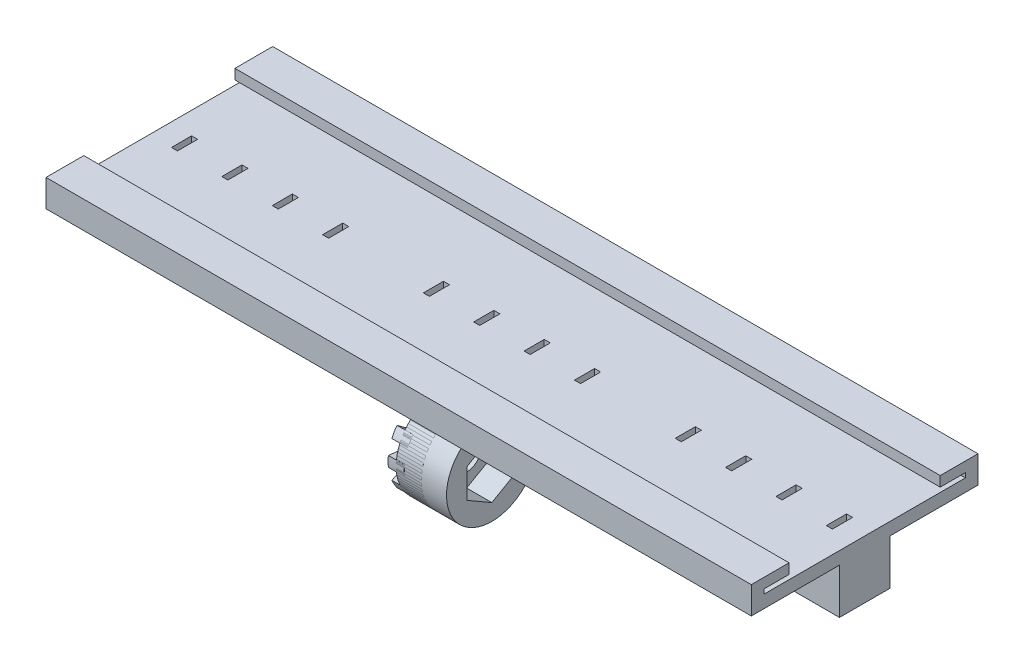
SolidWorks part; units mm, degrees
ref_plane "Alzado" through (0, 0, 0) normal (0, 0, 1) x (1, 0, 0)
ref_plane "Planta" through (0, 0, 0) normal (0, 1, 0) x (1, 0, 0)
ref_plane "Vista lateral" through (0, 0, 0) normal (1, 0, 0) x (0, 0, -1)
sketch "Croquis1" plane through (0, 0, 0) normal (0, 1, 0) x (1, 0, 0)
  line L1 (0, 0) -> (140, 0)
  line L2 (0, 0) -> (0, 45)
  line L3 (0, 45) -> (140, 45)
  line L4 (140, 0) -> (140, 45)
  dimension "D1" = 140
  dimension "D2" = 45
extrude "Saliente-Extruir1" add sketch "Croquis1" along normal blind 2.5
sketch "Croquis2" plane through (0, 2.5, 0) normal (0, 1, 0) x (1, 0, 0)
  line L0 (0, 42.5) -> (140, 42.5)
  line L1 (0, 45) -> (0, 0) construction
  line L2 (140, 0) -> (140, 45) construction
  line L3 (0, 22.5) -> (140, 22.5) construction
  line L4 (0, 45) -> (140, 45)
  line L5 (140, 45) -> (140, 42.5)
  line L6 (0, 45) -> (0, 42.5)
  line L7 (0, 0) -> (140, 0)
  line L8 (140, 0) -> (140, 2.5)
  line L9 (0, 2.5) -> (140, 2.5)
  line L10 (0, 0) -> (0, 2.5)
  dimension "D1" = 2.5
extrude "Saliente-Extruir2" add sketch "Croquis2" along normal blind 0.9
sketch "Croquis3" plane through (0, 3.4, 0) normal (0, 1, 0) x (1, 0, 0)
  line L0 (0, 45) -> (140, 45)
  line L1 (140, 45) -> (140, 37.5)
  line L2 (140, 2.5) -> (140, 42.5) construction
  line L3 (140, 37.5) -> (0, 37.5)
  line L4 (0, 42.5) -> (0, 2.5) construction
  line L5 (0, 37.5) -> (0, 45)
  line L6 (0, 22.5) -> (140, 22.5) construction
  line L7 (140, 7.5) -> (0, 7.5)
  line L8 (140, 0) -> (140, 7.5)
  line L9 (0, 0) -> (140, 0)
  line L10 (0, 7.5) -> (0, 0)
  dimension "D1" = 7.5
extrude "Saliente-Extruir3" add sketch "Croquis3" along normal blind 2
sketch "Croquis4" plane through (0, 0, 0) normal (0, -1, 0) x (1, 0, 0)
  line L0 (0, -22.5) -> (140, -22.5) construction
  line L1 (0, -45) -> (0, 0) construction
  line L2 (140, 0) -> (140, -45) construction
  line L4 (0, -27.5) -> (140, -27.5)
  line L5 (0, -27.5) -> (0, -17.5)
  line L6 (0, -17.5) -> (140, -17.5)
  line L7 (140, -27.5) -> (140, -17.5)
  line L8 (1.5, -26) -> (138.5, -26)
  line L9 (1.5, -26) -> (1.5, -19)
  line L10 (1.5, -19) -> (138.5, -19)
  line L11 (138.5, -26) -> (138.5, -19)
  point P10 (140, -22.5)
  point P15 (138.5, -22.5)
  dimension "D1" = 10
  dimension "D2" = 137
  dimension "D3" = 7
  dimension "D4" = 1.5
extrude "Saliente-Extruir4" add sketch "Croquis4" along normal blind 9
ref_plane "Plano1" through (70, 0, 0) normal (1, 0, 0) x (0, 0, -1)
sketch "Croquis6" plane through (70, 0, 0) normal (1, 0, 0) x (0, 0, -1)
  line L0 (17.5, -9) -> (-0.5, -9) construction
  line L1 (17.5, -9) -> (18.5, -9)
  line L2 (27.5, -9) -> (17.5, -9) construction
  line L3 (18.5, -9) -> (18.5, 1)
  line L4 (18.5, 1) -> (8.5, 1)
  line L5 (8.5, 1) -> (8.5, 0)
  line L7 (8.5, -14.75) -> (13.4796, -11.875)
  line L8 (13.4796, -11.875) -> (13.4796, -6.125)
  line L9 (13.4796, -6.125) -> (8.5, -3.25)
  line L10 (8.5, -3.25) -> (3.5204, -6.125)
  line L11 (3.5204, -6.125) -> (3.5204, -11.875)
  line L12 (3.5204, -11.875) -> (8.5, -14.75)
  circle A0 centre (8.5, -9) radius 9 construction
  circle A1 centre (8.5, -9) radius 5.75 construction
  circle A2 centre (8.5, -9) radius 4.9796 construction
  arc A3 (8.5, 0) -> (17.5, -9) centre (8.5, -9) ccw
  dimension "D1" = 18
  dimension "D5" = 11.5
  dimension "D6" = 9.9593
  dimension "D2" = 18
  dimension "D3" = 10
  dimension "D4" = 10
extrude "Saliente-Extruir5" add sketch "Croquis6" along normal blind 10
sketch "Croquis7" plane through (70, 0, 0) normal (-1, 0, 0) x (0, 0, 1)
  line L0 (-8.5, -18) -> (-8.5, 0) construction
  line L1 (-8.5, -9) -> (-7.1125, 3.1779) construction
  line L2 (-8.5, -9) -> (-9.8875, 3.1779) construction
  line L3 (-9.1792, -3.0386) -> (-9.5188, -0.0579)
  line L4 (-7.8208, -3.0386) -> (-7.4812, -0.0579)
  line L5 (-4.9311, -4.1769) -> (-3.1466, -1.7653)
  line L6 (-6.1075, -3.4976) -> (-4.9113, -0.7465)
  line L7 (-2.9976, -6.6075) -> (-0.2465, -5.4113)
  line L8 (-3.6769, -5.4311) -> (-1.2653, -3.6466)
  line L9 (-2.5386, -9.6792) -> (0.4421, -10.0188)
  line L10 (-2.5386, -8.3208) -> (0.4421, -7.9812)
  line L11 (-3.6769, -12.5689) -> (-1.2653, -14.3534)
  line L12 (-2.9976, -11.3925) -> (-0.2465, -12.5887)
  line L13 (-6.1075, -14.5024) -> (-4.9113, -17.2535)
  line L14 (-4.9311, -13.8231) -> (-3.1466, -16.2347)
  line L15 (-9.1792, -14.9614) -> (-9.5188, -17.9421)
  line L16 (-7.8208, -14.9614) -> (-7.4812, -17.9421)
  line L17 (-12.0689, -13.8231) -> (-13.8534, -16.2347)
  line L18 (-10.8925, -14.5024) -> (-12.0887, -17.2535)
  line L19 (-14.0024, -11.3925) -> (-16.7535, -12.5887)
  line L20 (-13.3231, -12.5689) -> (-15.7347, -14.3534)
  line L21 (-14.4614, -8.3208) -> (-17.4421, -7.9812)
  line L22 (-14.4614, -9.6792) -> (-17.4421, -10.0188)
  line L23 (-13.3231, -5.4311) -> (-15.7347, -3.6466)
  line L24 (-14.0024, -6.6075) -> (-16.7535, -5.4113)
  line L25 (-10.8925, -3.4976) -> (-12.0887, -0.7465)
  line L26 (-12.0689, -4.1769) -> (-13.8534, -1.7653)
  arc A0 (-17.5, -9) -> (-8.5, 0) centre (-8.5, -9) ccw construction
  circle A1 centre (-8.5, -9) radius 9 construction
  circle A2 centre (-8.5, -9) radius 3 construction
  circle A3 centre (-8.5, -9) radius 6 construction
  arc A4 (-9.1792, -3.0386) -> (-7.8208, -3.0386) centre (-8.5, -9) cw
  arc A5 (-9.5188, -0.0579) -> (-7.4812, -0.0579) centre (-8.5, -9) cw
  arc A6 (-4.9113, -0.7465) -> (-3.1466, -1.7653) centre (-8.5, -9) cw
  arc A7 (-6.1075, -3.4976) -> (-4.9311, -4.1769) centre (-8.5, -9) cw
  arc A8 (-1.2653, -3.6466) -> (-0.2465, -5.4113) centre (-8.5, -9) cw
  arc A9 (-3.6769, -5.4311) -> (-2.9976, -6.6075) centre (-8.5, -9) cw
  arc A10 (0.4421, -7.9812) -> (0.4421, -10.0188) centre (-8.5, -9) cw
  arc A11 (-2.5386, -8.3208) -> (-2.5386, -9.6792) centre (-8.5, -9) cw
  arc A12 (-0.2465, -12.5887) -> (-1.2653, -14.3534) centre (-8.5, -9) cw
  arc A13 (-2.9976, -11.3925) -> (-3.6769, -12.5689) centre (-8.5, -9) cw
  arc A14 (-3.1466, -16.2347) -> (-4.9113, -17.2535) centre (-8.5, -9) cw
  arc A15 (-4.9311, -13.8231) -> (-6.1075, -14.5024) centre (-8.5, -9) cw
  arc A16 (-7.4812, -17.9421) -> (-9.5188, -17.9421) centre (-8.5, -9) cw
  arc A17 (-7.8208, -14.9614) -> (-9.1792, -14.9614) centre (-8.5, -9) cw
  arc A18 (-12.0887, -17.2535) -> (-13.8534, -16.2347) centre (-8.5, -9) cw
  arc A19 (-10.8925, -14.5024) -> (-12.0689, -13.8231) centre (-8.5, -9) cw
  arc A20 (-15.7347, -14.3534) -> (-16.7535, -12.5887) centre (-8.5, -9) cw
  arc A21 (-13.3231, -12.5689) -> (-14.0024, -11.3925) centre (-8.5, -9) cw
  arc A22 (-17.4421, -10.0188) -> (-17.4421, -7.9812) centre (-8.5, -9) cw
  arc A23 (-14.4614, -9.6792) -> (-14.4614, -8.3208) centre (-8.5, -9) cw
  arc A24 (-16.7535, -5.4113) -> (-15.7347, -3.6466) centre (-8.5, -9) cw
  arc A25 (-14.0024, -6.6075) -> (-13.3231, -5.4311) centre (-8.5, -9) cw
  arc A26 (-13.8534, -1.7653) -> (-12.0887, -0.7465) centre (-8.5, -9) cw
  arc A27 (-12.0689, -4.1769) -> (-10.8925, -3.4976) centre (-8.5, -9) cw
  point P19 (0, 0)
  point P64 (-8.5, -9)
  dimension "D1" = 18
  dimension "D2" = 6
  dimension "D4" = 12
  dimension "D5" = 12
  dimension "D3" = 6.5
extrude "Saliente-Extruir20" add sketch "Croquis7" along normal mid plane 3.2 separate body
ref_plane "Plano3" through (75, 0, 0) normal (1, 0, 0) x (0, 0, -1)
sketch "Croquis9" plane through (75, 0, 0) normal (1, 0, 0) x (0, 0, -1)
  line L0 (-0.5, -9) -> (17.5, -9) construction
  arc A0 (8.5, 0) -> (17.5, -9) centre (8.5, -9) ccw construction
  circle A1 centre (8.5, -9) radius 9
  circle A2 centre (8.5, -9) radius 3
  dimension "D1" = 6
extrude "Saliente-Extruir24" add sketch "Croquis9" against normal blind 5 separate body
sketch "Croquis10" plane through (0, 0, 0) normal (0, -1, 0) x (1, 0, 0)
  line L0 (0, -22.5) -> (140, -22.5) construction
  line L1 (0, -17.5) -> (0, -27.5) construction
  line L2 (140, -27.5) -> (140, -17.5) construction
  line L3 (0, -22.5) -> (70, -22.5) construction
  line L4 (25, -22.5) -> (25, -53.1388) construction
  line L5 (34.4, -20.5) -> (35.6, -20.5)
  line L6 (34.4, -20.5) -> (34.4, -24.5)
  line L7 (34.4, -24.5) -> (35.6, -24.5)
  line L8 (35.6, -20.5) -> (35.6, -24.5)
  line L9 (34.4, -20.5) -> (35.6, -24.5) construction
  line L10 (34.4, -24.5) -> (35.6, -20.5) construction
  line L12 (24.4, -20.5) -> (25.6, -20.5)
  line L13 (24.4, -20.5) -> (24.4, -24.5)
  line L14 (24.4, -24.5) -> (25.6, -24.5)
  line L15 (25.6, -20.5) -> (25.6, -24.5)
  line L16 (24.4, -20.5) -> (25.6, -24.5) construction
  line L17 (24.4, -24.5) -> (25.6, -20.5) construction
  line L18 (14.4, -20.5) -> (15.6, -20.5)
  line L19 (14.4, -20.5) -> (14.4, -24.5)
  line L20 (14.4, -24.5) -> (15.6, -24.5)
  line L21 (15.6, -20.5) -> (15.6, -24.5)
  line L22 (14.4, -20.5) -> (15.6, -24.5) construction
  line L23 (14.4, -24.5) -> (15.6, -20.5) construction
  line L24 (70, -22.5) -> (70, -65.2648) construction
  line L25 (4.4, -20.5) -> (5.6, -20.5)
  line L26 (4.4, -20.5) -> (4.4, -24.5)
  line L27 (4.4, -24.5) -> (5.6, -24.5)
  line L28 (5.6, -20.5) -> (5.6, -24.5)
  line L29 (4.4, -20.5) -> (5.6, -24.5) construction
  line L30 (4.4, -24.5) -> (5.6, -20.5) construction
  line L31 (70, -12.87) -> (70, 12.87) construction
  line L32 (135.6, -24.5) -> (134.4, -20.5) construction
  line L33 (135.6, -20.5) -> (134.4, -24.5) construction
  line L34 (125.6, -24.5) -> (124.4, -20.5) construction
  line L35 (125.6, -20.5) -> (124.4, -24.5) construction
  line L36 (115.6, -24.5) -> (114.4, -20.5) construction
  line L37 (115.6, -20.5) -> (114.4, -24.5) construction
  line L38 (105.6, -24.5) -> (104.4, -20.5) construction
  line L39 (105.6, -20.5) -> (104.4, -24.5) construction
  line L40 (134.4, -20.5) -> (134.4, -24.5)
  line L41 (135.6, -24.5) -> (134.4, -24.5)
  line L42 (135.6, -20.5) -> (135.6, -24.5)
  line L43 (135.6, -20.5) -> (134.4, -20.5)
  line L44 (124.4, -20.5) -> (124.4, -24.5)
  line L45 (125.6, -24.5) -> (124.4, -24.5)
  line L46 (125.6, -20.5) -> (125.6, -24.5)
  line L47 (125.6, -20.5) -> (124.4, -20.5)
  line L48 (114.4, -20.5) -> (114.4, -24.5)
  line L49 (115.6, -24.5) -> (114.4, -24.5)
  line L50 (115.6, -20.5) -> (115.6, -24.5)
  line L51 (115.6, -20.5) -> (114.4, -20.5)
  line L52 (104.4, -20.5) -> (104.4, -24.5)
  line L53 (105.6, -24.5) -> (104.4, -24.5)
  line L54 (105.6, -20.5) -> (105.6, -24.5)
  line L55 (105.6, -20.5) -> (104.4, -20.5)
  point P6 (35, -22.5)
  point P18 (15, -22.5)
  point P23 (5, -22.5)
  point P47 (135, -22.5)
  point P48 (125, -22.5)
  point P49 (105, -22.5)
  dimension "D1" = 4
  dimension "D2" = 1.2
  dimension "D3" = 35
  dimension "D4" = 25
  dimension "D5" = 1.2
  dimension "D6" = 4
  dimension "D7" = 1.2
  dimension "D8" = 4
  dimension "D9" = 15
  dimension "D10" = 1.2
  dimension "D11" = 4
  dimension "D12" = 5
extrude "Cortar-Extruir1" cut sketch "Croquis10" against normal blind 10
sketch "Croquis12" plane through (0, 0, 0) normal (0, -1, 0) x (1, 0, 0)
  line L0 (0, -22.5) -> (140, -22.5) construction
  line L1 (0, -17.5) -> (0, -27.5) construction
  line L2 (140, -27.5) -> (140, -17.5) construction
  line L3 (84.4, -20.5) -> (85.6, -20.5)
  line L4 (84.4, -20.5) -> (84.4, -24.5)
  line L5 (84.4, -24.5) -> (85.6, -24.5)
  line L6 (85.6, -20.5) -> (85.6, -24.5)
  line L7 (84.4, -20.5) -> (85.6, -24.5) construction
  line L8 (84.4, -24.5) -> (85.6, -20.5) construction
  line L9 (74.4, -20.5) -> (75.6, -20.5)
  line L10 (74.4, -20.5) -> (74.4, -24.5)
  line L11 (74.4, -24.5) -> (75.6, -24.5)
  line L12 (75.6, -20.5) -> (75.6, -24.5)
  line L13 (74.4, -20.5) -> (75.6, -24.5) construction
  line L14 (74.4, -24.5) -> (75.6, -20.5) construction
  line L15 (64.4, -20.5) -> (65.6, -20.5)
  line L16 (64.4, -20.5) -> (64.4, -24.5)
  line L17 (64.4, -24.5) -> (65.6, -24.5)
  line L18 (65.6, -20.5) -> (65.6, -24.5)
  line L19 (64.4, -20.5) -> (65.6, -24.5) construction
  line L20 (64.4, -24.5) -> (65.6, -20.5) construction
  line L21 (54.4, -20.5) -> (55.6, -20.5)
  line L22 (54.4, -20.5) -> (54.4, -24.5)
  line L23 (54.4, -24.5) -> (55.6, -24.5)
  line L24 (55.6, -20.5) -> (55.6, -24.5)
  line L25 (54.4, -20.5) -> (55.6, -24.5) construction
  line L26 (54.4, -24.5) -> (55.6, -20.5) construction
  line L27 (55, -22.5) -> (85, -22.5) construction
  line L28 (65, -22.5) -> (75, -22.5) construction
  point P6 (85, -22.5)
  point P15 (65, -22.5)
  point P20 (55, -22.5)
  point P27 (70, -22.5)
  point P28 (70, -22.5)
  point P31 (70, -22.5)
  dimension "D1" = 4
  dimension "D2" = 1.2
  dimension "D3" = 1.2
  dimension "D4" = 4
  dimension "D5" = 1.2
  dimension "D6" = 4
  dimension "D7" = 1.2
  dimension "D8" = 4
  dimension "D9" = 30
  dimension "D10" = 10
extrude "Cortar-Extruir2" cut sketch "Croquis12" against normal blind 10
